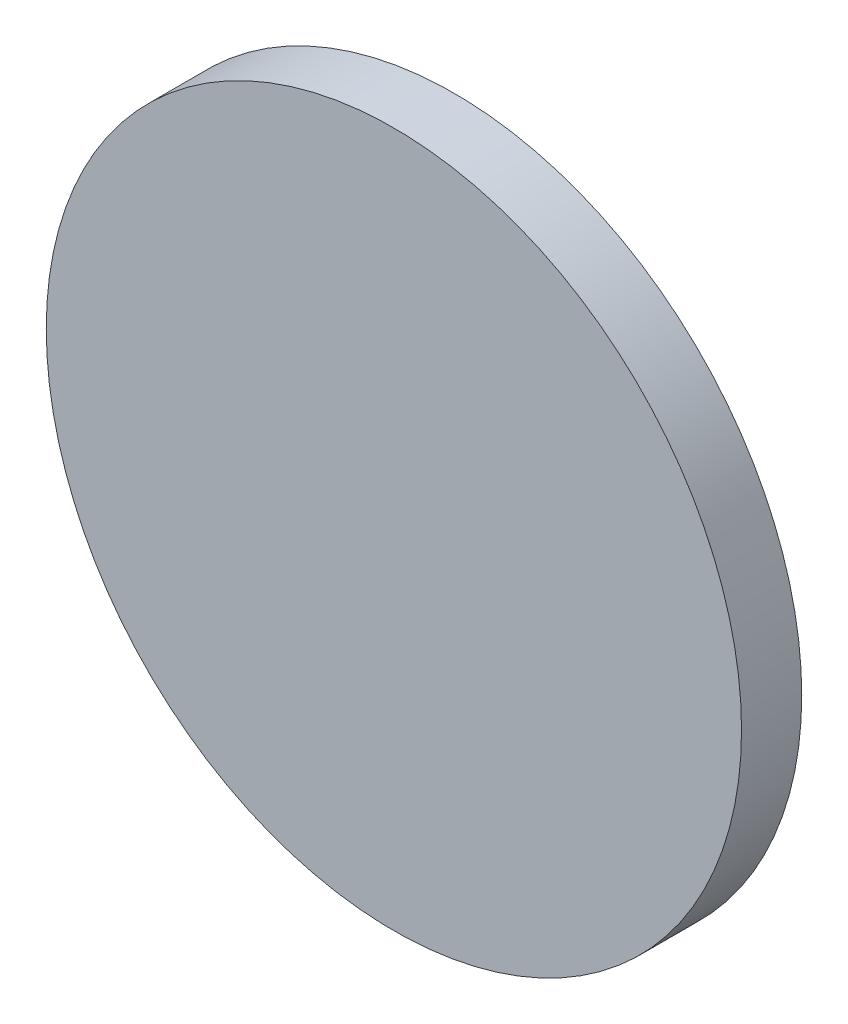
SolidWorks part; units mm, degrees
ref_plane "Front Plane" through (0, 0, 0) normal (0, 0, 1) x (1, 0, 0)
ref_plane "Top Plane" through (0, 0, 0) normal (0, 1, 0) x (1, 0, 0)
ref_plane "Right Plane" through (0, 0, 0) normal (1, 0, 0) x (0, 0, -1)
sketch "Sketch1" plane through (0, 0, 0) normal (0, 0, 1) x (1, 0, 0)
  circle A0 centre (0, 0) radius 6.35
  dimension "D1" = 12.7
extrude "Boss-Extrude1" add sketch "Sketch1" along normal blind 1.1
